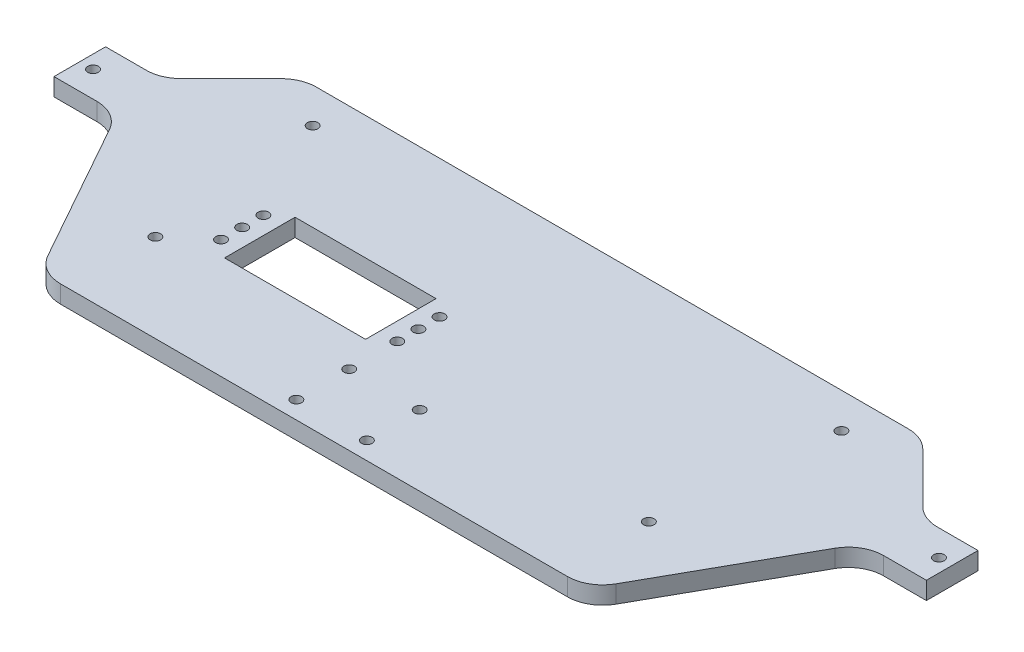
SolidWorks part; units mm, degrees
ref_plane "Alzado" through (0, 0, 0) normal (0, 0, 1) x (1, 0, 0)
ref_plane "Planta" through (0, 0, 0) normal (0, 1, 0) x (1, 0, 0)
ref_plane "Vista lateral" through (0, 0, 0) normal (1, 0, 0) x (0, 0, -1)
sketch "Croquis1" plane through (0, 0, 0) normal (0, 1, 0) x (1, 0, 0)
  line L0 (-27.8825, 0) -> (38.5584, 0) construction
  line L1 (-88.1, 42.3182) -> (88.1, 42.3182)
  line L2 (-77.75, -42.3182) -> (77.75, -42.3182)
  line L3 (-88.1, 42.3182) -> (-108.1, 22.3182)
  line L4 (-108.1, 22.3182) -> (-127.75, 22.3182)
  line L5 (0, 0) -> (0, 27.7067) construction
  line L6 (-127.75, 22.3182) -> (-127.75, 7.6818)
  line L7 (-127.75, 7.6818) -> (-105.75, 7.6818)
  line L8 (-105.75, 7.6818) -> (-77.75, -42.3182)
  line L9 (88.1, 42.3182) -> (108.1, 22.3182)
  line L10 (108.1, 22.3182) -> (127.75, 22.3182)
  line L11 (127.75, 22.3182) -> (127.75, 7.6818)
  line L12 (127.75, 7.6818) -> (105.75, 7.6818)
  line L13 (105.75, 7.6818) -> (77.75, -42.3182)
  dimension "D1" = 255.5
  dimension "D2" = 84.6363
  dimension "D3" = 19.65
  dimension "D4" = 22
  dimension "D5" = 22
  dimension "D6" = 50
  dimension "D7" = 50
  dimension "D8" = 50
  dimension "D9" = 20
  dimension "D10" = 20
  dimension "D11" = 19.65
extrude "Saliente-Extruir1" add sketch "Croquis1" along normal blind 5
fillet "Redondeo1" radius 10 8 edges at (88.1, 2.5, -42.3182) (-88.1, 2.5, -42.3182) (-77.75, 2.5, 42.3182) (77.75, 2.5, 42.3182) (108.1, 2.5, -22.3182) (105.75, 2.5, -7.6818) (-105.75, 2.5, -7.6818) (-108.1, 2.5, -22.3182)
sketch "Croquis2" plane through (0, 5, 0) normal (0, 1, 0) x (1, 0, 0)
  line L0 (0, 0) -> (0, -87.7887) construction
  line L1 (-119.9961, 22.3182) -> (-119.9961, 40.4374) construction
  line L2 (-112.2421, 22.3182) -> (-127.75, 22.3182) construction
  line L3 (-127.75, 15) -> (-123.2915, 15) construction
  line L4 (-127.75, 22.3182) -> (-127.75, 7.6818) construction
  line L5 (119.9961, 22.3182) -> (119.9961, 29.1715) construction
  line L6 (127.75, 22.3182) -> (112.2421, 22.3182) construction
  line L7 (115.6048, 15) -> (126.3231, 15) construction
  line L8 (83.9579, 42.3182) -> (-83.9579, 42.3182) construction
  line L9 (-55, 7.3182) -> (-15, 7.3182)
  line L10 (-71.8888, -42.3182) -> (71.8888, -42.3182) construction
  line L11 (-15, 7.3182) -> (-15, -12.6818)
  line L12 (-15, -12.6818) -> (-55, -12.6818)
  line L13 (-55, -12.6818) -> (-55, 7.3182)
  line L14 (-55, -2.6818) -> (-2.6959, -2.6818) construction
  line L15 (-35, 7.3182) -> (-35, 33.9331) construction
  line L16 (-10, -2.6818) -> (-10, 14.1752) construction
  line L17 (-60, -2.6818) -> (-60, -5.5648) construction
  circle A0 centre (70, -17.3182) radius 1.5
  circle A1 centre (-70, -17.3182) radius 1.5
  circle A2 centre (-119.9961, 15) radius 1.5
  circle A3 centre (119.9961, 15) radius 1.5
  circle A4 centre (-75, 32.3182) radius 1.5
  circle A5 centre (75, 32.3182) radius 1.5
  circle A6 centre (-10, -22.3182) radius 1.5
  circle A7 centre (10, -22.3182) radius 1.5
  circle A8 centre (-10, -37.3182) radius 1.5
  circle A9 centre (10, -37.3182) radius 1.5
  circle A10 centre (-60, -2.6818) radius 1.5
  circle A11 centre (-10, -2.6818) radius 1.5
  circle A12 centre (-60, 3.3182) radius 1.5
  circle A13 centre (-60, -8.6818) radius 1.5
  circle A14 centre (-10, 3.3182) radius 1.5
  circle A15 centre (-10, -8.6818) radius 1.5
  dimension "D1" = 3
  dimension "D2" = 3
  dimension "D7" = 3
  dimension "D8" = 3
  dimension "D10" = 3
  dimension "D11" = 3
  dimension "D17" = 3
  dimension "D18" = 3
  dimension "D19" = 3
  dimension "D20" = 3
  dimension "D25" = 50
  dimension "D27" = 3
  dimension "D28" = 3
  dimension "D29" = 3
  dimension "D30" = 3
  dimension "D31" = 3
  dimension "D32" = 3
  dimension "D3" = 75
  dimension "D4" = 75
  dimension "D5" = 10
  dimension "D6" = 10
  dimension "D9" = 140
  dimension "D12" = 25
  dimension "D13" = 20
  dimension "D14" = 20
  dimension "D15" = 5
  dimension "D16" = 15
  dimension "D21" = 40
  dimension "D22" = 20
  dimension "D23" = 30
  dimension "D24" = 35
  dimension "D26" = 50
  dimension "D33" = 6
  dimension "D34" = 6
  dimension "D35" = 6
  dimension "D36" = 6
extrude "Cortar-Extruir1" cut sketch "Croquis2" against normal through all
sketch "Croquis3" plane through (0, 5, 0) normal (0, 1, 0) x (1, 0, 0)
  line L0 (-123.75, 22.3182) -> (-123.75, 7.6818)
  line L1 (-112.2421, 22.3182) -> (-127.75, 22.3182) construction
  line L2 (-127.75, 7.6818) -> (-111.6112, 7.6818) construction
  line L3 (-123.75, 7.6818) -> (-127.75, 7.6818)
  line L4 (-127.75, 7.6818) -> (-127.75, 22.3182)
  line L5 (-127.75, 22.3182) -> (-123.75, 22.3182)
  line L6 (127.75, 7.6818) -> (127.75, 22.3182)
  line L7 (127.75, 22.3182) -> (123.75, 22.3182)
  line L8 (127.75, 22.3182) -> (112.2421, 22.3182) construction
  line L9 (123.75, 22.3182) -> (123.75, 7.6818)
  line L10 (111.6112, 7.6818) -> (127.75, 7.6818) construction
  line L11 (123.75, 7.6818) -> (127.75, 7.6818)
  dimension "D1" = 4
  dimension "D2" = 4
extrude "Cortar-Extruir2" cut sketch "Croquis3" against normal through all
